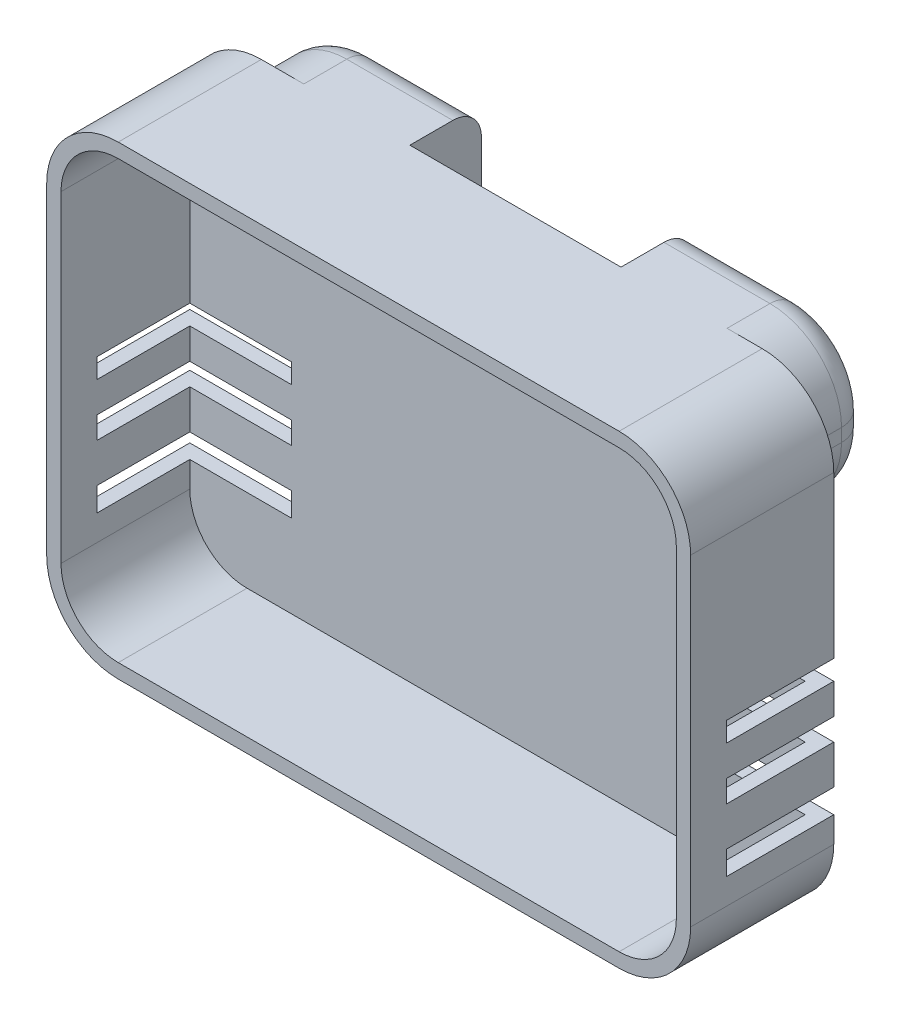
SolidWorks part; units mm, degrees
ref_plane "Plano frontal" through (0, 0, 0) normal (0, 0, 1) x (1, 0, 0)
ref_plane "Plano superior" through (0, 0, 0) normal (0, 1, 0) x (1, 0, 0)
ref_plane "Plano direito" through (0, 0, 0) normal (1, 0, 0) x (0, 0, -1)
sketch "Esboço1" plane through (0, 0, 0) normal (0, 0, 1) x (1, 0, 0)
  line L1 (-35, 32.5) -> (35, 32.5)
  line L2 (-45, 22.5) -> (-45, -22.5)
  line L3 (-35, -32.5) -> (35, -32.5)
  line L4 (45, 22.5) -> (45, -22.5)
  line L5 (-45, 32.5) -> (45, -32.5) construction
  line L6 (-45, -32.5) -> (45, 32.5) construction
  arc A0 (-45, -22.5) -> (-35, -32.5) centre (-35, -22.5) ccw
  arc A1 (35, -32.5) -> (45, -22.5) centre (35, -22.5) ccw
  arc A2 (35, 32.5) -> (45, 22.5) centre (35, 22.5) cw
  arc A3 (-35, 32.5) -> (-45, 22.5) centre (-35, 22.5) ccw
  point P0 (0, 0)
  dimension "D1" = 10
  dimension "D2" = 90
  dimension "D3" = 65
extrude "Ressalto-extrusão1" add sketch "Esboço1" along normal blind 20
shell "Casca1" thickness 2
ref_plane "Plano1" through (0, 0, 0) normal (0, 0, -1) x (-1, 0, 0)
sketch "Esboço2" plane through (0, 0, 0) normal (0, 0, -1) x (-1, 0, 0)
  line L0 (0, 73.7322) -> (0, -73.7322) construction
  line L1 (-103.6002, 21.5877) -> (105.6202, 21.5877) construction
  line L2 (35, 32.5) -> (-35, 32.5) construction
  line L3 (-30.086, 32.5) -> (-15.2688, 32.5)
  line L4 (-40.086, 22.5) -> (-40.086, 20.6754)
  line L5 (-30.086, 10.6754) -> (-15.2688, 10.6754)
  line L6 (-15.2688, 32.5) -> (-15.2688, 10.6754)
  line L7 (-40.086, 32.5) -> (-15.2688, 10.6754) construction
  line L8 (-40.086, 10.6754) -> (-15.2688, 32.5) construction
  line L9 (14.2436, 32.5) -> (29.0609, 32.5)
  line L10 (14.2436, 32.5) -> (14.2436, 10.6754)
  line L11 (14.2436, 10.6754) -> (29.0609, 10.6754)
  line L12 (39.0609, 22.5) -> (39.0609, 20.6754)
  line L13 (14.2436, 32.5) -> (39.0609, 10.6754) construction
  line L14 (14.2436, 10.6754) -> (39.0609, 32.5) construction
  arc A0 (29.0609, 10.6754) -> (39.0609, 20.6754) centre (29.0609, 20.6754) ccw
  arc A1 (29.0609, 32.5) -> (39.0609, 22.5) centre (29.0609, 22.5) cw
  arc A2 (-40.086, 20.6754) -> (-30.086, 10.6754) centre (-30.086, 20.6754) ccw
  arc A3 (-30.086, 32.5) -> (-40.086, 22.5) centre (-30.086, 22.5) ccw
  point P5 (-27.6774, 21.5877)
  point P10 (26.6523, 21.5877)
  dimension "D1" = 10
  dimension "D2" = 0
extrude "Ressalto-extrusão2" add sketch "Esboço2" along normal blind 10
fillet "Filete1" radius 4 10 edges at (-21.6523, 10.6754, -10) (-36.132, 13.6043, -10) (-39.0609, 21.5877, -10) (-36.132, 29.5711, -10) (22.6774, 10.6754, -10) (37.1571, 13.6043, -10) (40.086, 21.5877, -10) (37.1571, 29.5711, -10) (-21.6523, 32.5, -10) (22.6774, 32.5, -10)
ref_plane "Plano3" through (0, 10.6754, 0) normal (0, -1, 0) x (-1, 0, 0)
ref_plane "Plano4" through (0, 10.6754, 0) normal (0, -1, 0) x (-1, 0, 0)
sketch "Esboço5" plane through (0, 10.6754, 0) normal (0, -1, 0) x (-1, 0, 0)
  line L0 (-30.086, 6) -> (-40.086, 6) construction
  line L1 (-36.5391, 6) -> (-12.5534, 6)
  line L2 (-36.5391, 6) -> (-36.5391, 0)
  line L3 (-36.5391, 0) -> (-12.5534, 0)
  line L4 (-12.5534, 6) -> (-12.5534, 0)
  line L5 (35, 0) -> (-35, 0) construction
extrude "Corte-extrusão1" cut sketch "Esboço5" against normal blind 15
sketch "Esboço6" plane through (0, 10.6754, 0) normal (0, -1, 0) x (1, 0, 0)
  line L0 (-35.75, 0) -> (35.75, 0) construction
  line L1 (-35.1658, 0) -> (-10.668, 0)
  line L2 (-35.1658, 0) -> (-35.1658, -6.0323)
  line L3 (-35.1658, -6.0323) -> (-10.668, -6.0323)
  line L4 (-10.668, 0) -> (-10.668, -6.0323)
extrude "Corte-extrusão2" cut sketch "Esboço6" against normal blind 15
sketch "Esboço7" plane through (0, 0, 0) normal (0, 0, -1) x (-1, 0, 0)
  line L1 (-64.7983, 0) -> (-26.3057, 0)
  line L2 (-64.7983, 0) -> (-64.7983, -2.7559)
  line L3 (-64.7983, -2.7559) -> (-26.3057, -2.7559)
  line L4 (-26.3057, 0) -> (-26.3057, -2.7559)
  line L5 (-64.7983, -7.0328) -> (-26.3057, -7.0328)
  line L6 (-64.7983, -7.0328) -> (-64.7983, -10.1217)
  line L7 (-64.7983, -10.1217) -> (-26.3057, -10.1217)
  line L8 (-26.3057, -7.0328) -> (-26.3057, -10.1217)
  line L9 (-64.7983, -15.5868) -> (-26.3057, -15.5868)
  line L10 (-64.7983, -15.5868) -> (-64.7983, -18.9133)
  line L11 (-64.7983, -18.9133) -> (-26.3057, -18.9133)
  line L12 (-26.3057, -15.5868) -> (-26.3057, -18.9133)
  line L13 (28.8196, 0) -> (63.5105, 0)
  line L14 (28.8196, 0) -> (28.8196, -2.7559)
  line L15 (28.8196, -2.7559) -> (63.5105, -2.7559)
  line L16 (63.5105, 0) -> (63.5105, -2.7559)
  line L17 (28.8196, -7.0328) -> (63.5105, -7.0328)
  line L18 (28.8196, -7.0328) -> (28.8196, -10.1217)
  line L19 (28.8196, -10.1217) -> (63.5105, -10.1217)
  line L20 (63.5105, -7.0328) -> (63.5105, -10.1217)
  line L21 (28.8196, -15.5868) -> (63.5105, -15.5868)
  line L22 (28.8196, -15.5868) -> (28.8196, -18.9133)
  line L23 (28.8196, -18.9133) -> (63.5105, -18.9133)
  line L24 (63.5105, -15.5868) -> (63.5105, -18.9133)
extrude "Corte-extrusão3" cut sketch "Esboço7" against normal blind 15 and the other way blind 15
